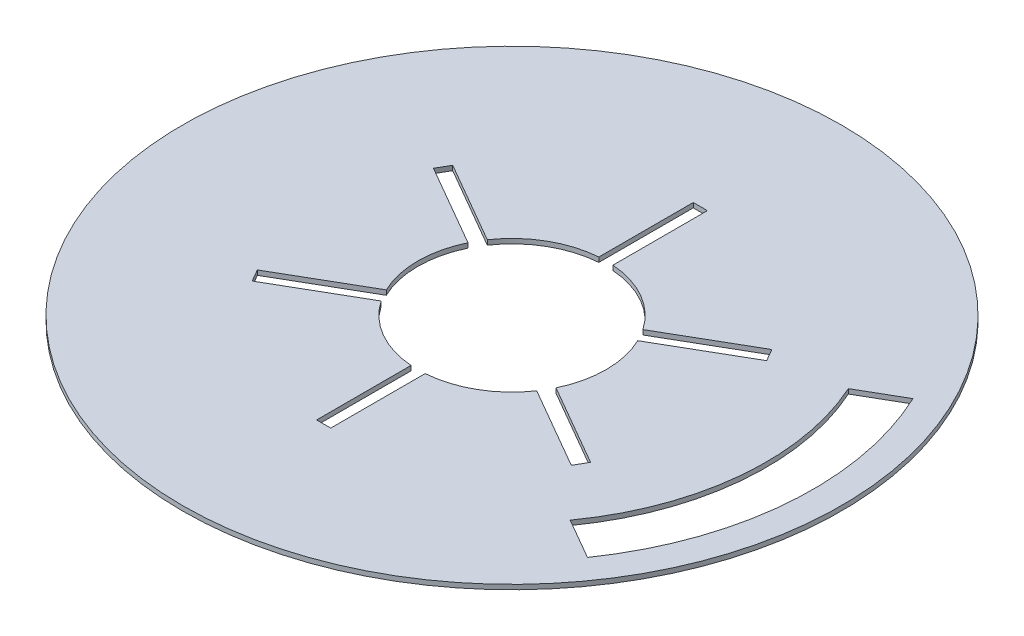
SolidWorks part; units mm, degrees
ref_plane "Ön Düzlem" through (0, 0, 0) normal (0, 0, 1) x (1, 0, 0)
ref_plane "Üst Düzlem" through (0, 0, 0) normal (0, 1, 0) x (1, 0, 0)
ref_plane "Sağ Düzlem" through (0, 0, 0) normal (1, 0, 0) x (0, 0, -1)
sketch "Çizim1" plane through (0, 0, 0) normal (0, 1, 0) x (1, 0, 0)
  line L0 (82.6086, 56.3544) -> (169.4551, 106.4952)
  line L1 (-150, 55.7008) -> (-96.8246, 25)
  line L2 (-7.5, 99.7184) -> (-7.5, 200)
  line L3 (-7.5, 200) -> (7.5, 200)
  line L4 (7.5, 99.7184) -> (7.5, 200)
  line L5 (169.4551, 106.4952) -> (176.9551, 93.5048)
  line L6 (90.1086, 43.364) -> (176.9551, 93.5048)
  line L7 (-150, 55.7008) -> (-150, -55.7008)
  line L8 (90.1086, -43.364) -> (176.9551, -93.5048)
  line L9 (176.9551, -93.5048) -> (169.4551, -106.4952)
  line L10 (82.6086, -56.3544) -> (169.4551, -106.4952)
  line L11 (-150, -55.7008) -> (-96.8246, -25)
  line L12 (7.5, -99.7184) -> (7.5, -200)
  line L13 (7.5, -200) -> (-7.5, -200)
  line L14 (-7.5, -99.7184) -> (-7.5, -200)
  line L15 (-26.7617, 157.7542) -> (-26.7617, 96.3525)
  line L16 (-82.6086, -56.3544) -> (-169.4551, -106.4952)
  line L17 (-169.4551, -106.4952) -> (-176.9551, -93.5048)
  line L18 (-90.1086, -43.364) -> (-176.9551, -93.5048)
  line L19 (-26.7617, 157.7542) -> (-123.2383, 102.0534)
  line L20 (-90.1086, 43.364) -> (-176.9551, 93.5048)
  line L21 (-176.9551, 93.5048) -> (-169.4551, 106.4952)
  line L22 (-82.6086, 56.3544) -> (-169.4551, 106.4952)
  line L23 (-123.2383, 102.0534) -> (-70.0629, 71.3525)
  line L24 (246.0563, 111.159) -> (289.5381, 136.2632)
  line L25 (123.2383, 102.0534) -> (70.0629, 71.3525)
  line L26 (123.2383, 102.0534) -> (26.7617, 157.7542)
  line L27 (26.7617, 157.7542) -> (26.7617, 96.3525)
  line L28 (150, -55.7008) -> (96.8246, -25)
  line L29 (150, -55.7008) -> (150, 55.7008)
  line L30 (150, 55.7008) -> (96.8246, 25)
  line L31 (26.7617, -157.7542) -> (26.7617, -96.3525)
  line L32 (26.7617, -157.7542) -> (123.2383, -102.0534)
  line L33 (123.2383, -102.0534) -> (70.0629, -71.3525)
  line L34 (-123.2383, -102.0534) -> (-70.0629, -71.3525)
  line L35 (-123.2383, -102.0534) -> (-26.7617, -157.7542)
  line L36 (-26.7617, -157.7542) -> (-26.7617, -96.3525)
  line L37 (219.2946, -157.5115) -> (262.7765, -182.6158)
  circle A0 centre (0, 0) radius 350
  arc A1 (-90.1086, 43.364) -> (-90.1086, -43.364) centre (0, 0) ccw
  arc A2 (-7.5, 99.7184) -> (-82.6086, 56.3544) centre (0, 0) ccw
  arc A3 (82.6086, 56.3544) -> (7.5, 99.7184) centre (0, 0) ccw
  arc A4 (90.1086, -43.364) -> (90.1086, 43.364) centre (0, 0) ccw
  arc A5 (-82.6086, -56.3544) -> (-7.5, -99.7184) centre (0, 0) ccw
  arc A6 (7.5, -99.7184) -> (82.6086, -56.3544) centre (0, 0) ccw
  arc A7 (246.0563, 111.159) -> (219.2946, -157.5115) centre (0, 0) cw
  arc A8 (289.5381, 136.2632) -> (262.7765, -182.6158) centre (0, 0) cw
  point P57 (0, 0)
  point P69 (0, 0)
  dimension "D1" = 700
  dimension "D2" = 200
  dimension "D11" = 80
  dimension "D12" = 50
  dimension "D3" = 15
  dimension "D4" = 7.5
  dimension "D5" = 200
  dimension "D8" = 50
  dimension "D9" = 150
  dimension "D10" = 6
  dimension "D7" = 6
extrude "Yükseklik-Ekstrüzyon1" add sketch "Çizim1" along normal blind 5 contours A0 A6 L12 L13 L14 A5 L36 L35 L34 L16 L17 L18 A1 L11 L7 L1 L20 L21 L22 A2 L23 L19 L15 L2 L3 L4 A3 L27 L26 L25 L0 L5 L6 A4 L30 L29 L28 L8 L9 L10 L33 L32 L31 | A2 L15 L19 L23 | A3 L25 L26 L27 | A4 L28 L29 L30 | A6 L31 L32 L33 | A5 L34 L35 L36 | A1 L1 L7 L11
